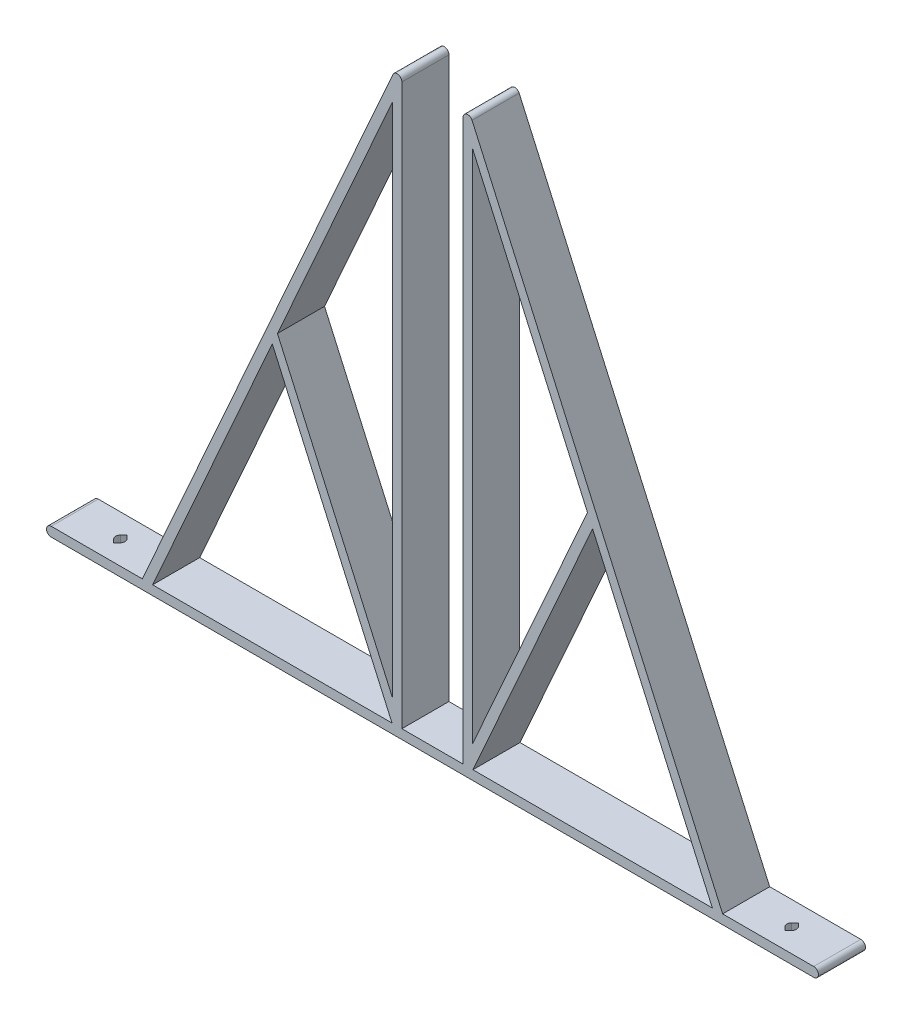
SolidWorks part; units mm, degrees
ref_plane "Front Plane" through (0, 0, 0) normal (0, 0, 1) x (1, 0, 0)
ref_plane "Top Plane" through (0, 0, 0) normal (0, 1, 0) x (1, 0, 0)
ref_plane "Right Plane" through (0, 0, 0) normal (1, 0, 0) x (0, 0, -1)
sketch "Sketch2" plane through (0, 0, 0) normal (0, 0, 1) x (1, 0, 0)
  line L0 (7.5949, 1) -> (58.4593, 1)
  line L2 (33.0271, 58.0442) -> (58.4593, 1)
  line L5 (31.9322, 60.5) -> (7.5, 5.6988)
  line L6 (7.5, 5.6988) -> (7.5, 115.3012)
  line L7 (7.5, 115.3012) -> (31.9322, 60.5)
  line L8 (0, -1) -> (60, -1)
  line L9 (60, -1) -> (80, -1)
  line L11 (5.5, 1) -> (5.5, 124.6988)
  line L12 (5.5, 124.6988) -> (60.649, 1)
  line L13 (0, 1) -> (5.5, 1)
  line L14 (60.649, 1) -> (80, 1)
  line L20 (33.0271, 58.0442) -> (7.5949, 1)
  line L25 (0, -1) -> (-2, -1)
  line L27 (-2, 1) -> (0, 1)
  line L29 (-35.0271, 58.0442) -> (-9.5949, 1)
  line L30 (-62.649, 1) -> (-82, 1)
  line L31 (-2, 1) -> (-7.5, 1)
  line L32 (-7.5, 124.6988) -> (-62.649, 1)
  line L33 (-7.5, 1) -> (-7.5, 124.6988)
  line L34 (-62, -1) -> (-82, -1)
  line L35 (-2, -1) -> (-62, -1)
  line L36 (-9.5, 115.3012) -> (-33.9322, 60.5)
  line L37 (-9.5, 5.6988) -> (-9.5, 115.3012)
  line L38 (-33.9322, 60.5) -> (-9.5, 5.6988)
  line L39 (-35.0271, 58.0442) -> (-60.4593, 1)
  line L40 (-9.5949, 1) -> (-60.4593, 1)
  arc A5 (80, -1) -> (80, 1) centre (80, 0) ccw
  arc A6 (-82, -1) -> (-82, 1) centre (-82, 0) cw
  dimension "D1" = 1
  dimension "D2" = 5.5
  dimension "D3" = 7.5
  dimension "D4" = 7.5949
  dimension "D5" = 31.9322
  dimension "D6" = 33.0271
  dimension "D7" = 5.6988
  dimension "D8" = 60
  dimension "D9" = 60.649
  dimension "D10" = 80
  dimension "D14" = 124.6988
extrude "Boss-Extrude1" add sketch "Sketch2" along normal blind 10
sketch "Sketch3" plane through (0, 1, 0) normal (0, 1, 0) x (1, 0, 0)
  line L0 (-72.3245, -6.4142) -> (-72.3245, -3.5858) construction
  line L1 (-72.3245, -3.5858) -> (-73.0316, -4.2929)
  line L2 (-73.0316, -4.2929) -> (-73.0316, -5.7071) construction
  line L3 (-73.0316, -5.7071) -> (-72.3245, -6.4142)
  line L4 (-72.3245, -3.5858) -> (-71.6174, -4.2929)
  line L5 (-71.6174, -4.2929) -> (-71.6174, -5.7071) construction
  line L6 (-71.6174, -5.7071) -> (-72.3245, -6.4142)
  line L9 (-1, 0) -> (-1, -10) construction
  line L10 (5.5, 0) -> (-7.5, 0) construction
  line L11 (5.5, -10) -> (-7.5, -10) construction
  line L12 (69.6174, -4.2929) -> (69.6174, -5.7071) construction
  line L13 (71.0316, -4.2929) -> (71.0316, -5.7071) construction
  line L14 (70.3245, -6.4142) -> (70.3245, -3.5858) construction
  line L15 (69.6174, -5.7071) -> (70.3245, -6.4142)
  line L16 (70.3245, -3.5858) -> (69.6174, -4.2929)
  line L17 (71.0316, -5.7071) -> (70.3245, -6.4142)
  line L18 (70.3245, -3.5858) -> (71.0316, -4.2929)
  line L19 (-62.649, -10) -> (-82, -10) construction
  line L20 (-82, -10) -> (-82, 0) construction
  arc A0 (-71.6174, -5.7071) -> (-71.6174, -4.2929) centre (-72.3245, -5) ccw
  arc A1 (-73.0316, -4.2929) -> (-73.0316, -5.7071) centre (-72.3245, -5) ccw
  arc A2 (71.0316, -4.2929) -> (71.0316, -5.7071) centre (70.3245, -5) cw
  arc A3 (69.6174, -5.7071) -> (69.6174, -4.2929) centre (70.3245, -5) cw
  point P1 (0, 0)
  point P11 (-72.3245, -10)
  point P26 (-82, -5)
  dimension "D1" = 2
  dimension "D2" = 45
extrude "Cut-Extrude1" cut sketch "Sketch3" against normal up to next
fillet "Fillet1" radius 1 1 edges at (5.5, 124.6988, 5)
fillet "Fillet2" radius 1 1 edges at (-7.5, 124.6988, 5)
